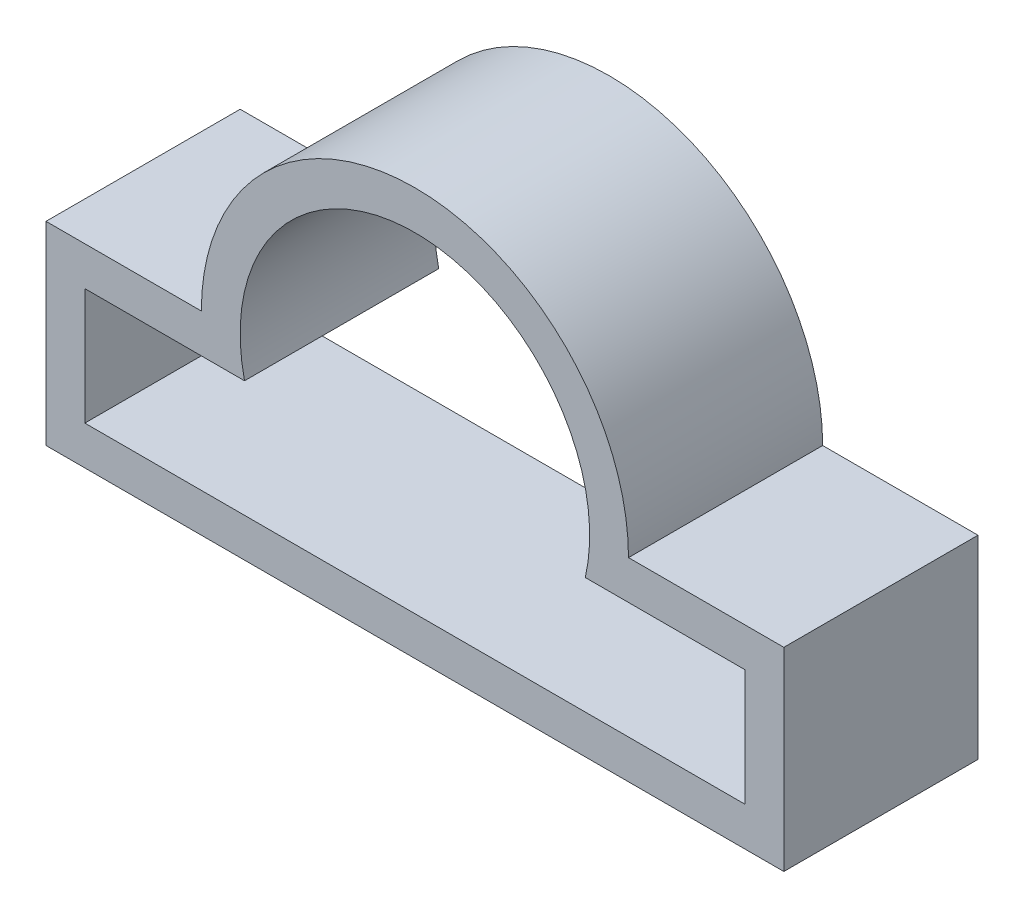
SolidWorks part; units mm, degrees
ref_plane "Front Plane" through (0, 0, 0) normal (0, 0, 1) x (1, 0, 0)
ref_plane "Top Plane" through (0, 0, 0) normal (0, 1, 0) x (1, 0, 0)
ref_plane "Right Plane" through (0, 0, 0) normal (1, 0, 0) x (0, 0, -1)
sketch "Sketch1" plane through (0, 0, 0) normal (0, 0, 1) x (1, 0, 0)
  line L0 (19, 0) -> (-19, 0)
  line L1 (-19, 0) -> (-19, 10)
  line L2 (-19, 10) -> (-11, 10)
  line L3 (11, 10) -> (19, 10)
  line L4 (19, 10) -> (19, 0)
  arc A0 (-11, 10) -> (11, 10) centre (0, 10) cw
  point P7 (0, 0)
  point P9 (0, 0)
  point P10 (0, 0)
  dimension "D3" = 11
  dimension "D1" = 38
  dimension "D2" = 10
extrude "Extrude-Thin1" add sketch "Sketch1" along normal blind 10 thin
